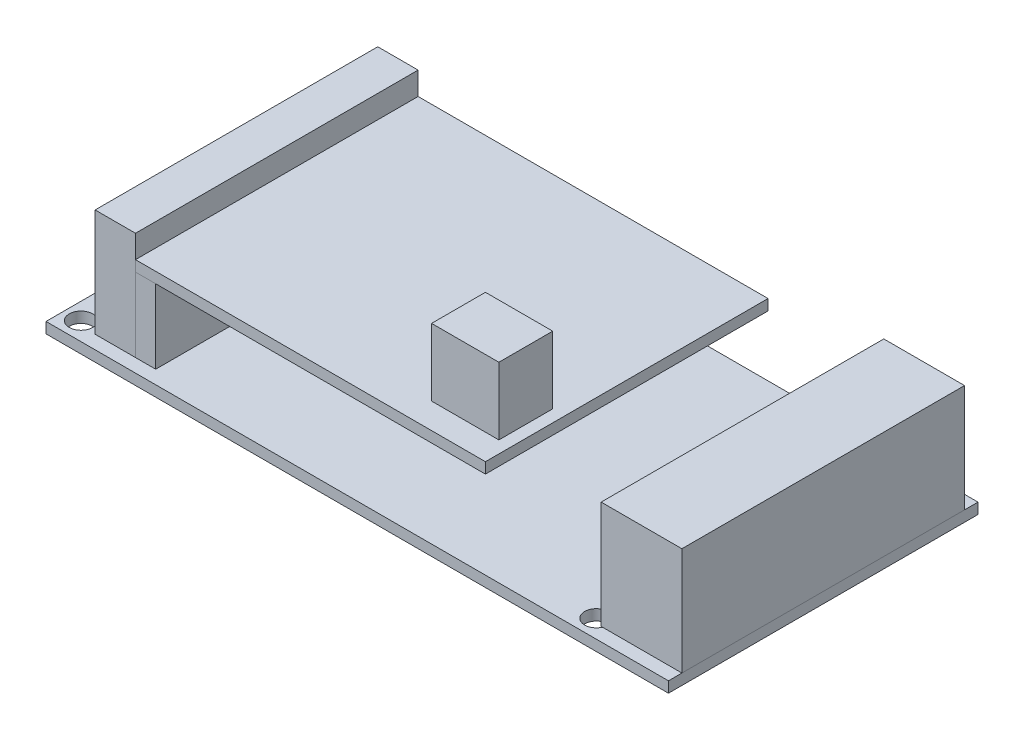
SolidWorks part; units mm, degrees
material "VITON"
ref_plane "Přední" through (0, 0, 0) normal (0, 0, 1) x (1, 0, 0)
ref_plane "Horní" through (0, 0, 0) normal (0, 1, 0) x (1, 0, 0)
ref_plane "Pravá" through (0, 0, 0) normal (1, 0, 0) x (0, 0, -1)
sketch "Skica1" plane through (0, 0, 0) normal (0, 1, 0) x (1, 0, 0)
  line L1 (46.25, 23) -> (-46.25, 23)
  line L2 (46.25, 23) -> (46.25, -23)
  line L3 (46.25, -23) -> (-46.25, -23)
  line L4 (-46.25, 23) -> (-46.25, -23)
  line L5 (46.25, 23) -> (-46.25, -23) construction
  line L6 (46.25, -23) -> (-46.25, 23) construction
  point P0 (0, 0)
  dimension "D1" = 92.5
  dimension "D2" = 46
extrude "Přidat vysunutím1" add sketch "Skica1" along normal blind 1.6
hole_wizard "Ø3.5 (3.5) průměr díry1" positions "Skica3" profile "Skica2" hole size "Ø3.5" standard "DIN" end condition through all
sketch "Skica3" plane through (0, 1.6, 0) normal (0, 1, 0) x (1, 0, 0)
  line L0 (-43.75, 20.3) -> (-43.75, -20.3) construction
  line L1 (-43.75, -20.3) -> (32.85, -20.3) construction
  line L2 (32.85, -20.3) -> (32.85, 20.3) construction
  line L3 (32.85, 20.3) -> (-43.75, 20.3) construction
  line L6 (-43.75, 0) -> (0, 0) construction
  line L9 (-46.25, 23) -> (-46.25, -23) construction
  point P0 (-43.75, 20.3)
  point P2 (-43.75, -20.3)
  point P4 (32.85, -20.3)
  point P6 (32.85, 20.3)
  dimension "D1" = 40.6
  dimension "D2" = 76.6
  dimension "D3" = 2.5
sketch "Skica2" plane through (-43.75, 1.6, -20.3) normal (1, 0, 0) x (0, 0, 1)
  line L0 (0, 0) -> (0, 1.6)
  line L1 (0, 1.6) -> (1.75, 1.6)
  line L2 (1.75, 1.6) -> (1.75, 0)
  line L5 (1.75, 0) -> (0, 0)
  line L11 (0, -6.35) -> (0, 107.95) construction
  dimension "Průměr díry skrz" = 3.5
  dimension "Hloubka díry skrz" = 1.6
sketch "Skica4" plane through (0, 1.6, 0) normal (0, 1, 0) x (1, 0, 0)
  line L0 (-46.25, 23) -> (-46.25, -23) construction
  line L1 (-34.95, 21) -> (-40.95, 21)
  line L2 (-34.95, 21) -> (-34.95, -21)
  line L3 (-34.95, -21) -> (-40.95, -21)
  line L4 (-40.95, 21) -> (-40.95, -21)
  line L5 (-34.95, 21) -> (-40.95, -21) construction
  line L6 (-34.95, -21) -> (-40.95, 21) construction
  line L7 (-46.25, 0) -> (-37.95, 0) construction
  line L8 (46.25, -23) -> (46.25, 23) construction
  line L9 (34.25, -21) -> (46.25, -21)
  line L10 (34.25, -21) -> (34.25, 21)
  line L11 (34.25, 21) -> (46.25, 21)
  line L12 (46.25, -21) -> (46.25, 21)
  line L13 (34.25, -21) -> (46.25, 21) construction
  line L14 (34.25, 21) -> (46.25, -21) construction
  point P0 (-37.95, 0)
  point P9 (40.25, 0)
  dimension "D1" = 6
  dimension "D2" = 42
  dimension "D3" = 5.3
  dimension "D4" = 12
extrude "Přidat vysunutím2" add sketch "Skica4" along normal blind 16 separate body
sketch "Skica5" plane through (0, 1.6, 0) normal (0, 1, 0) x (1, 0, 0)
  line L1 (-31.95, -21) -> (-34.95, -21)
  line L2 (-31.95, -21) -> (-31.95, 21)
  line L3 (-31.95, 21) -> (-34.95, 21)
  line L4 (-34.95, -21) -> (-34.95, 21)
  line L5 (-31.95, -21) -> (-34.95, 21) construction
  line L6 (-31.95, 21) -> (-34.95, -21) construction
  point P0 (-33.45, 0)
  dimension "D1" = 3
extrude "Přidat vysunutím3" add sketch "Skica5" along normal blind 11 separate body
sketch "Skica6" plane through (0, 12.6, 0) normal (0, 1, 0) x (1, 0, 0)
  line L0 (-34.95, -21) -> (-31.95, -21) construction
  line L1 (-34.95, 21) -> (17.05, 21)
  line L2 (-34.95, 21) -> (-34.95, -21)
  line L3 (-34.95, -21) -> (17.05, -21)
  line L4 (17.05, 21) -> (17.05, -21)
  dimension "D1" = 52
extrude "Přidat vysunutím4" add sketch "Skica6" along normal blind 1.6 separate body
sketch "Skica7" plane through (0, 14.2, 0) normal (0, 1, 0) x (1, 0, 0)
  line L0 (-46.25, -23) -> (46.25, -23) construction
  line L1 (5.25, -9.2) -> (15.25, -9.2)
  line L2 (5.25, -9.2) -> (5.25, -17.2)
  line L3 (5.25, -17.2) -> (15.25, -17.2)
  line L4 (15.25, -9.2) -> (15.25, -17.2)
  line L5 (17.05, -21) -> (17.05, 21) construction
  dimension "D1" = 10
  dimension "D2" = 8
  dimension "D3" = 5.8
  dimension "D4" = 1.8
extrude "Přidat vysunutím5" add sketch "Skica7" along normal blind 10 separate body
